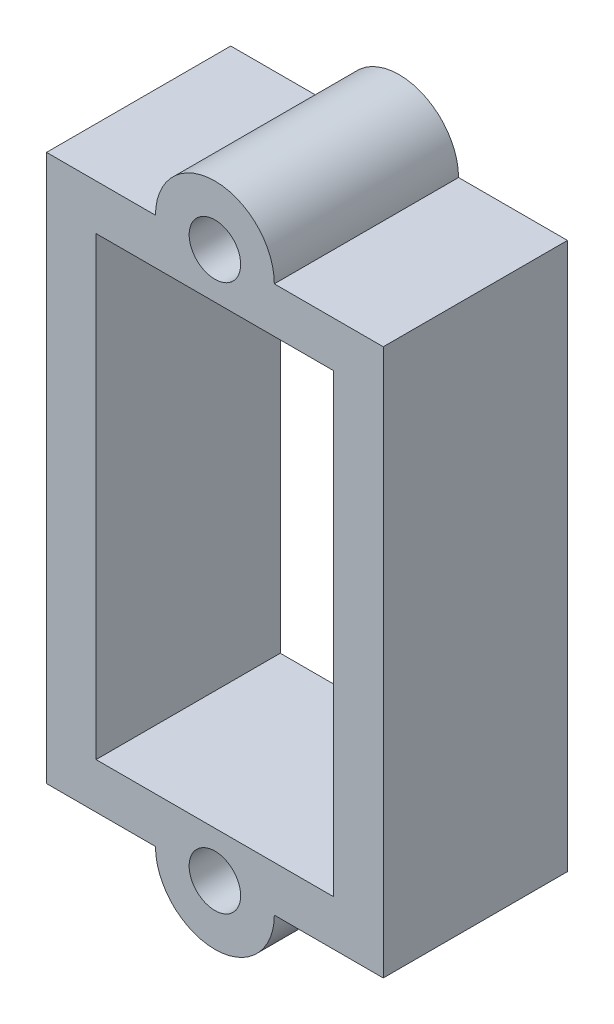
SolidWorks part; units mm, degrees
ref_plane "Front Plane" through (0, 0, 0) normal (0, 0, 1) x (1, 0, 0)
ref_plane "Top Plane" through (0, 0, 0) normal (0, 1, 0) x (1, 0, 0)
ref_plane "Right Plane" through (0, 0, 0) normal (1, 0, 0) x (0, 0, -1)
sketch "Sketch1" plane through (0, 0, 0) normal (0, 0, 1) x (1, 0, 0)
  line L0 (-6, 11.5) -> (6, 11.5)
  line L5 (-6, 11.5) -> (-6, -11.5)
  line L7 (-6, -11.5) -> (6, -11.5)
  line L8 (6, 11.5) -> (6, -11.5)
  line L13 (-6, 11.5) -> (6, -11.5) construction
  line L14 (-6, -11.5) -> (6, 11.5) construction
  line L15 (0, -13.8) -> (0, 13.8) construction
  line L16 (-3, 13.8) -> (-8.5, 13.8)
  line L17 (-8.5, 16.8) -> (8.5, 16.8) construction
  line L18 (-8.5, 16.8) -> (-8.5, -16.8) construction
  line L19 (-8.5, -16.8) -> (8.5, -16.8) construction
  line L20 (8.5, 16.8) -> (8.5, -16.8) construction
  line L21 (-8.5, 16.8) -> (8.5, -16.8) construction
  line L22 (-8.5, -16.8) -> (8.5, 16.8) construction
  line L23 (-8.5, 13.8) -> (-8.5, -13.8)
  line L24 (-8.5, -13.8) -> (-3, -13.8)
  line L25 (3, 13.8) -> (8.5, 13.8)
  line L26 (8.5, 13.8) -> (8.5, -13.8)
  line L27 (8.5, -13.8) -> (3, -13.8)
  circle A6 centre (0, 13.8) radius 1.3
  circle A7 centre (0, -13.8) radius 1.3
  arc A8 (-3, -13.8) -> (3, -13.8) centre (0, -13.8) ccw
  arc A9 (-3, 13.8) -> (3, 13.8) centre (0, 13.8) cw
  point P0 (0, 0)
  point P7 (0, 0)
  point P9 (0, 0)
  point P13 (0, 0)
  point P26 (0, 0)
  point P28 (0, 0)
  dimension "D1" = 2.6
  dimension "D2" = 23
  dimension "D5" = 27.6
  dimension "D3" = 12
  dimension "D4" = 2.5
  dimension "D6" = 3
extrude "Boss-Extrude1" add sketch "Sketch1" along normal blind 9.3
